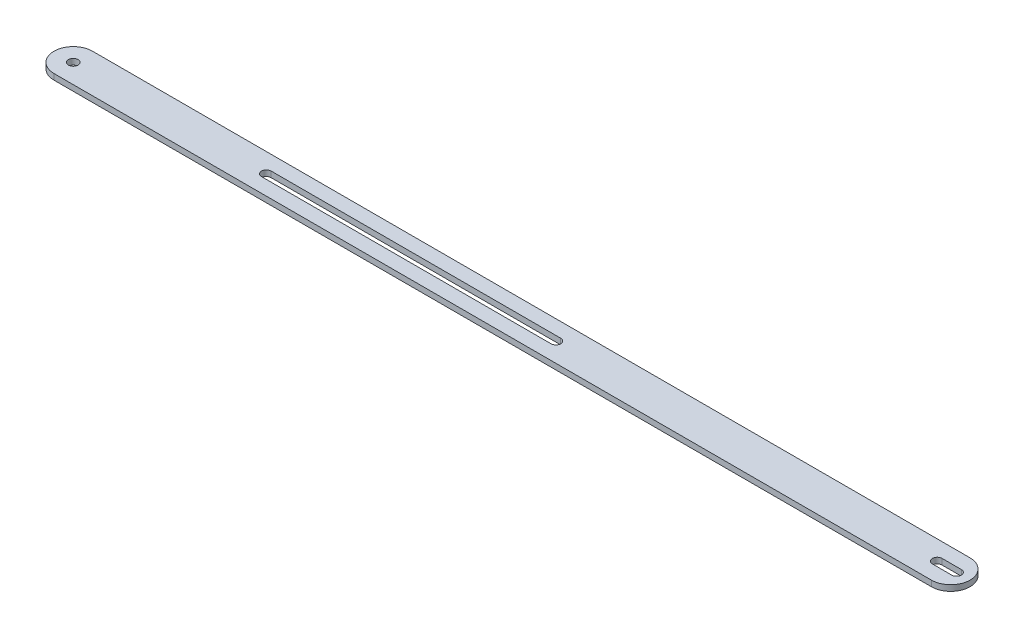
SolidWorks part; units mm, degrees
ref_plane "Front Plane" through (0, 0, 0) normal (0, 0, 1) x (1, 0, 0)
ref_plane "Top Plane" through (0, 0, 0) normal (0, 1, 0) x (1, 0, 0)
ref_plane "Right Plane" through (0, 0, 0) normal (1, 0, 0) x (0, 0, -1)
sketch "Sketch1" plane through (0, 0, 0) normal (0, 1, 0) x (1, 0, 0)
  line L0 (-227.25, 0) -> (227.25, 0) construction
  line L1 (-227.25, 10) -> (227.25, 10)
  line L2 (-227.25, -10) -> (227.25, -10)
  line L3 (230.25, 0) -> (220.25, 0) construction
  line L4 (230.25, -2.5) -> (220.25, -2.5)
  line L5 (230.25, 2.5) -> (220.25, 2.5)
  arc A0 (-227.25, 10) -> (-227.25, -10) centre (-227.25, 0) ccw
  arc A1 (227.25, -10) -> (227.25, 10) centre (227.25, 0) ccw
  circle A3 centre (-227.25, 0) radius 2.5
  arc A4 (230.25, -2.5) -> (230.25, 2.5) centre (230.25, 0) ccw
  arc A5 (220.25, 2.5) -> (220.25, -2.5) centre (220.25, 0) ccw
  point P2 (0, 0)
  point P12 (225.25, 0)
  point P17 (220.25, 0)
  point P18 (0, 0)
  point P19 (0, 0)
  dimension "D1" = 10
  dimension "D2" = 5
  dimension "D4" = 2.5
  dimension "D3" = 454.5
  dimension "D5" = 10
  dimension "D6" = 2
extrude "Boss-Extrude1" add sketch "Sketch1" along normal blind 3
sketch "Sketch2" plane through (0, 3, 0) normal (0, 1, 0) x (1, 0, 0)
  line L0 (-127.25, 0) -> (22.75, 0) construction
  line L1 (-127.25, 2.5) -> (22.75, 2.5)
  line L2 (-127.25, -2.5) -> (22.75, -2.5)
  arc A0 (-127.25, 2.5) -> (-127.25, -2.5) centre (-127.25, 0) ccw
  arc A1 (22.75, -2.5) -> (22.75, 2.5) centre (22.75, 0) ccw
  circle A2 centre (-227.25, 0) radius 2.5 construction
  point P2 (-52.25, 0)
  point P8 (0, 0)
  dimension "D1" = 2.5
  dimension "D2" = 150
  dimension "D3" = 100
extrude "Cut-Extrude1" cut sketch "Sketch2" against normal through all
